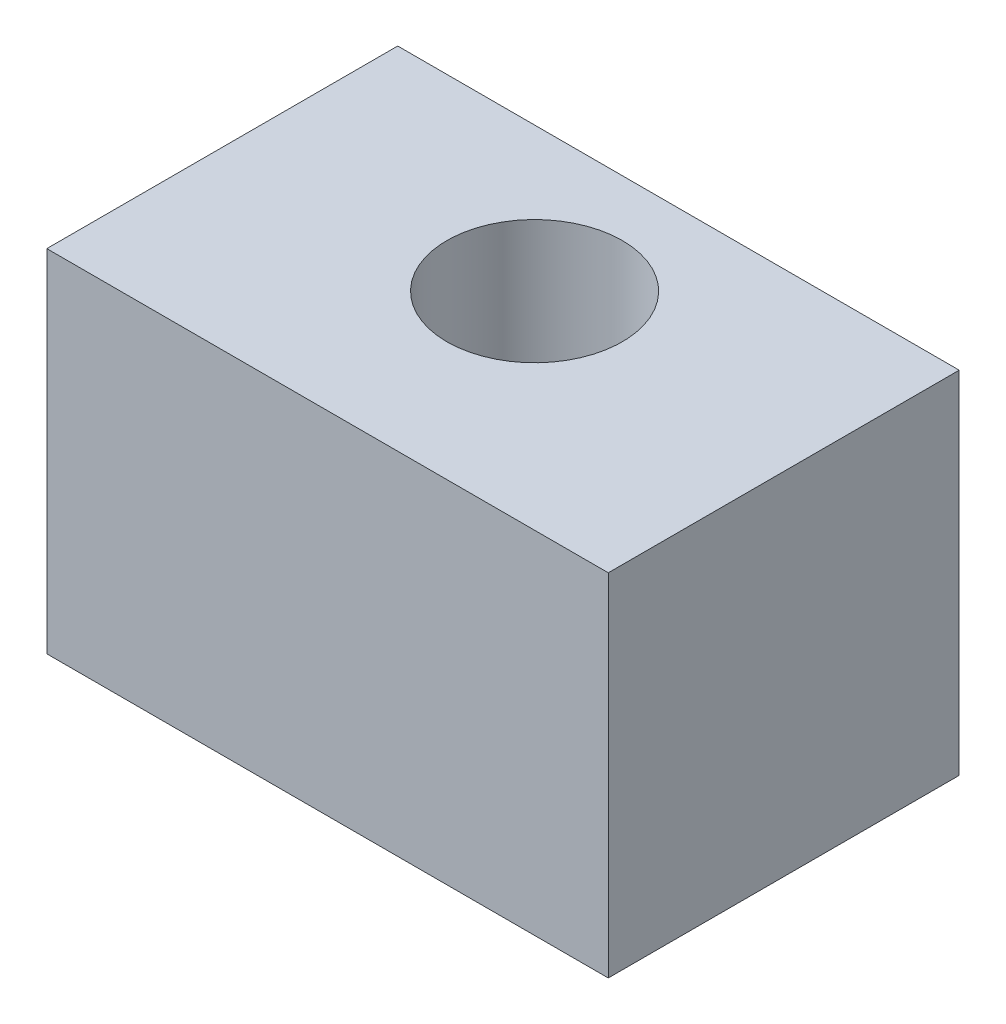
SolidWorks part; units mm, degrees
ref_plane "Front Plane" through (0, 0, 0) normal (0, 0, 1) x (1, 0, 0)
ref_plane "Top Plane" through (0, 0, 0) normal (0, 1, 0) x (1, 0, 0)
ref_plane "Right Plane" through (0, 0, 0) normal (1, 0, 0) x (0, 0, -1)
sketch "Sketch1" plane through (0, 0, 0) normal (0, 1, 0) x (1, 0, 0)
  line L1 (0, 0) -> (16, 0)
  line L2 (0, 0) -> (0, 10)
  line L3 (0, 10) -> (16, 10)
  line L4 (16, 0) -> (16, 10)
  line L5 (0, 0) -> (16, 10) construction
  line L6 (0, 10) -> (16, 0) construction
  circle A0 centre (8, 5.9) radius 2.5
  point P4 (8, 5)
  dimension "D1" = 5
  dimension "D2" = 5.9
  dimension "D3" = 10
  dimension "D4" = 16
  dimension "D5" = 8
extrude "Boss-Extrude1" add sketch "Sketch1" along normal blind 10
